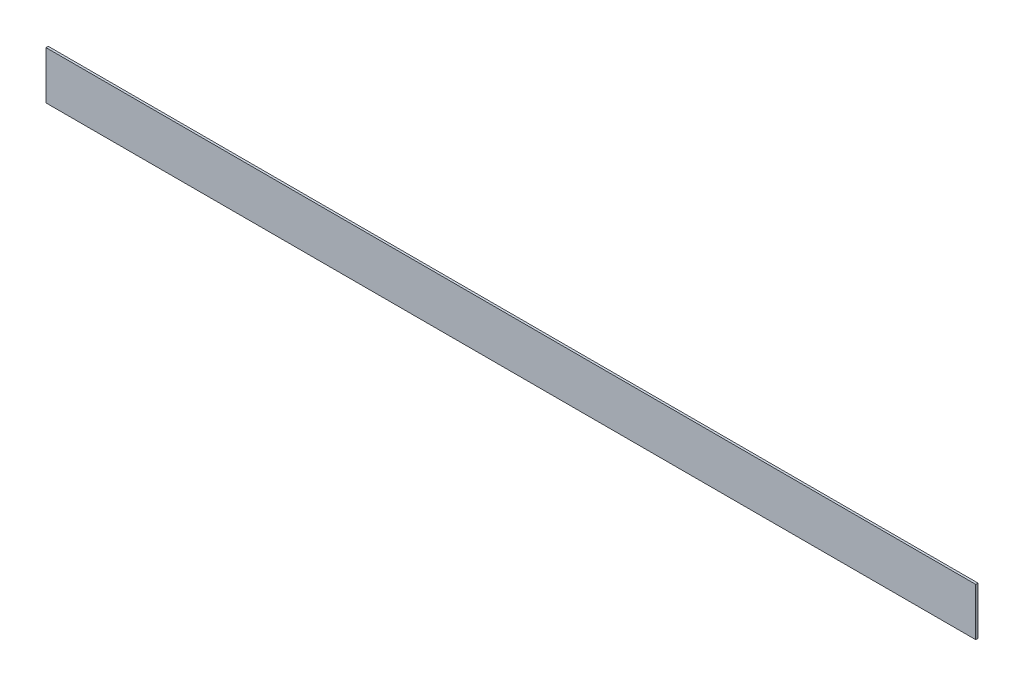
SolidWorks part; units mm, degrees
ref_plane "前视基准面" through (0, 0, 0) normal (0, 0, 1) x (1, 0, 0)
ref_plane "上视基准面" through (0, 0, 0) normal (0, 1, 0) x (1, 0, 0)
ref_plane "右视基准面" through (0, 0, 0) normal (1, 0, 0) x (0, 0, -1)
other "Configuration Table"
sketch "草图1" plane through (0, 0, 0) normal (0, 0, 1) x (1, 0, 0)
  line L1 (0, 0) -> (2056, 0)
  line L2 (0, 0) -> (0, 106)
  line L3 (0, 106) -> (2056, 106)
  line L4 (2056, 0) -> (2056, 106)
  dimension "D1" = 106
  dimension "D2" = 2056
extrude "凸台-拉伸1" add sketch "草图1" along normal blind 5
